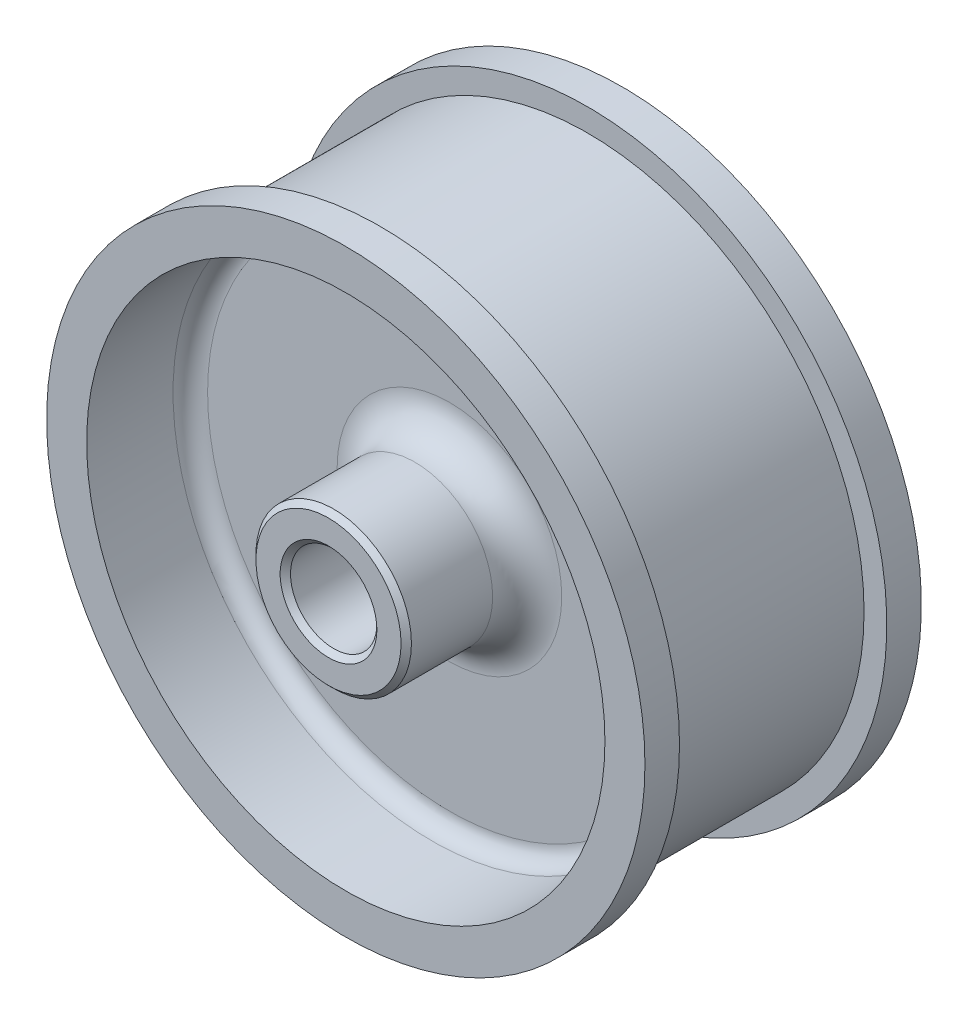
SolidWorks part; units mm, degrees
ref_plane "Front Plane" through (0, 0, 0) normal (0, 0, 1) x (1, 0, 0)
ref_plane "Top Plane" through (0, 0, 0) normal (0, 1, 0) x (1, 0, 0)
ref_plane "Right Plane" through (0, 0, 0) normal (1, 0, 0) x (0, 0, -1)
sketch "Sketch1" plane through (0, 0, 0) normal (0, 0, 1) x (1, 0, 0)
  line L0 (0, 15.397) -> (0, -15.993) construction
  line L1 (-21.4564, 0) -> (20.6618, 0) construction
  circle A0 centre (0, 0) radius 1.25
  circle A1 centre (0, 0) radius 2.25
  dimension "D1" = 4.5
  dimension "2" = 2.5
extrude "Boss-Extrude1" add sketch "Sketch1" along normal mid plane 9
sketch "Sketch2" plane through (0, 0, 0) normal (0, 0, 1) x (1, 0, 0)
  circle A0 centre (0, 0) radius 2.25
  circle A1 centre (0, 0) radius 7.6508
  dimension "4" = 4.5
extrude "Boss-Extrude2" add sketch "Sketch2" along normal mid plane 2
fillet "Fillet2" radius 1 1 edges at (2.25, 0, 1)
fillet "Fillet3" radius 1 1 edges at (2.25, 0, -1)
sketch "Sketch3" plane through (0, 0, 0) normal (0, 0, 1) x (1, 0, 0)
  circle A0 centre (0, 0) radius 7.5
  circle A1 centre (0, 0) radius 8
  dimension "D1" = 15
  dimension "D2" = 16
extrude "Boss-Extrude3" add sketch "Sketch3" along normal mid plane 6
fillet "Fillet4" radius 0.5 2 edges at (7.5, 0, -1) (7.5, 0, 1)
sketch "Sketch4" plane through (0, 0, 3) normal (0, 0, 1) x (1, 0, 0)
  circle A0 centre (0, 0) radius 7.5
  circle A1 centre (0, 0) radius 8.6583
  dimension "D1" = 17.3167
extrude "Boss-Extrude4" add sketch "Sketch4" along normal blind 1
sketch "Sketch5" plane through (0, 0, -3) normal (0, 0, -1) x (-1, 0, 0)
  circle A0 centre (0, 0) radius 7.5
  circle A1 centre (0, 0) radius 8.6583
extrude "Boss-Extrude5" add sketch "Sketch5" along normal blind 1
chamfer "Chamfer1" distance 0.15 angle 45 4 edges at (2.25, 0, -4.5) (1.25, 0, -4.5) (1.25, 0, 4.5) (2.25, 0, 4.5)
